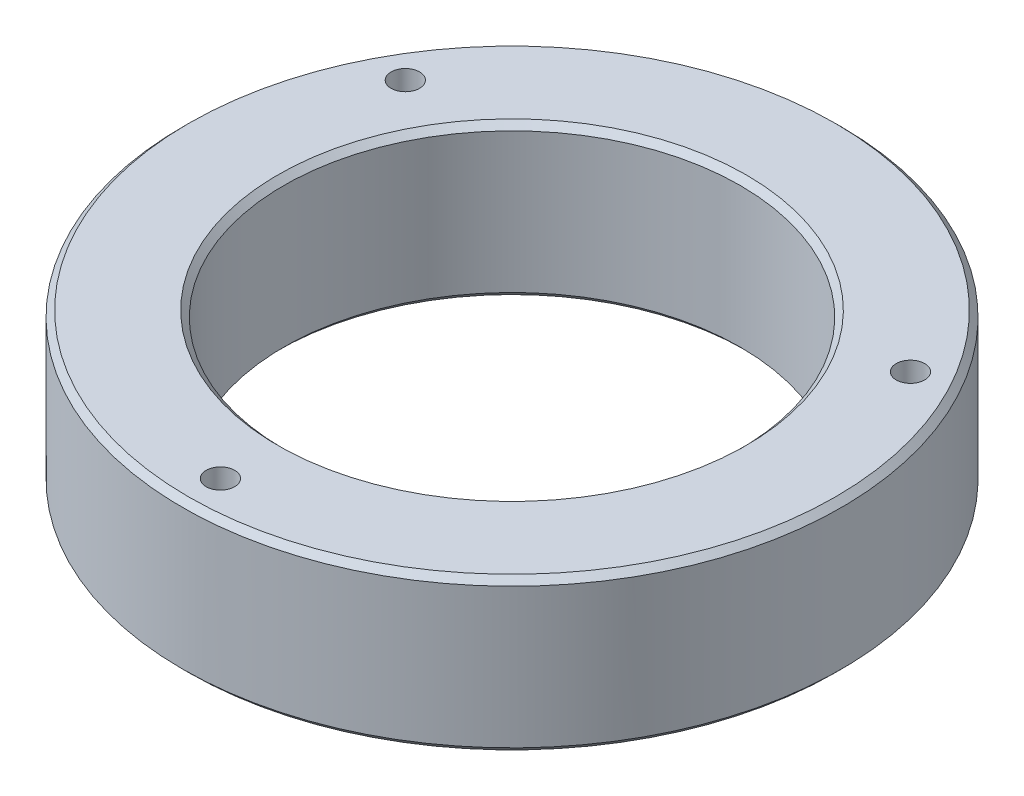
SolidWorks part; units mm, degrees
ref_plane "Front Plane" through (0, 0, 0) normal (1, 0, 0) x (0, 1, 0)
ref_plane "Top Plane" through (0, 0, 0) normal (0, 0, 1) x (0, 1, 0)
ref_plane "Right Plane" through (0, 0, 0) normal (0, 1, 0) x (-1, 0, 0)
sketch "Sketch1" plane through (0, 0, 0) normal (0, 0, 1) x (0, 1, 0)
  line L0 (-19.05, 82.5246) -> (19.05, 82.5246)
  line L1 (19.05, 82.5246) -> (19.05, 57.15)
  line L2 (19.05, 57.15) -> (-19.05, 57.15)
  line L3 (-19.05, 57.15) -> (-19.05, 82.5246)
  line L4 (-44.45, 0) -> (44.45, 0) construction
revolve "Revolve1" add sketch "Sketch1" angle 360 about L4
hole_wizard "CBORE for 1/4 Socket Head Cap Screw1" positions "Sketch3" profile "Sketch2" counterbore size "1/4" standard "ANSI Inch"
sketch "Sketch3" plane through (0, -19.05, 0) normal (0, -1, 0) x (-1, 0, 0)
  point P0 (0, -73.025)
  point P1 (-63.246, 36.5252)
  point P3 (63.246, 36.5252)
sketch "Sketch2" plane through (0, -19.05, 73.025) normal (1, 0, 0) x (0, 0, -1)
  line L0 (0, 0) -> (0, 40.2443)
  line L1 (0, 40.2443) -> (3.5687, 38.1)
  line L2 (3.5687, 38.1) -> (3.5687, 9.652)
  line L3 (3.5687, 9.652) -> (5.5626, 9.652)
  line L4 (5.5626, 9.652) -> (5.5626, 0)
  line L5 (5.5626, 0) -> (0, 0)
  line L10 (0, 40.2443) -> (-3.5687, 38.1) construction
  line L11 (0, -6.35) -> (0, 107.95) construction
  dimension "Hole Dia." = 7.1374
  dimension "Hole Depth" = 38.1
  dimension "C'Bore Dia." = 11.1252
  dimension "C'Bore Depth" = 9.652
  dimension "Drill Angle" = 118
hole_wizard "3/8-16 Tapped Hole2" positions "Sketch7" profile "Sketch6" tap size "3/8-16" standard "ANSI Inch"
sketch "Sketch7" plane through (0, -19.05, 0) normal (0, -1, 0) x (-1, 0, 0)
  point P0 (-69.85, 0)
  point P1 (69.85, 0)
sketch "Sketch6" plane through (69.85, -19.05, 0) normal (1, 0, 0) x (0, 0, -1)
  line L0 (0, 0) -> (0, 27.7847)
  line L1 (0, 27.7847) -> (3.9687, 25.4)
  line L2 (3.9687, 25.4) -> (3.9687, 0)
  line L5 (3.9687, 0) -> (0, 0)
  line L10 (0, 27.7847) -> (-3.9687, 25.4) construction
  line L11 (0, -6.35) -> (0, 107.95) construction
  dimension "Tap Drill Dia." = 7.9375
  dimension "Tap Drill Depth" = 25.4
  dimension "Drill Angle" = 118
cosmetic thread "Hole Thread3"
cosmetic thread "Hole Thread4"
chamfer "Chamfer1" distance 1.524 angle 45 4 edges at (0, 19.05, -57.15) (0, -19.05, -57.15) (0, 19.05, -82.5246) (0, -19.05, -82.5246)
